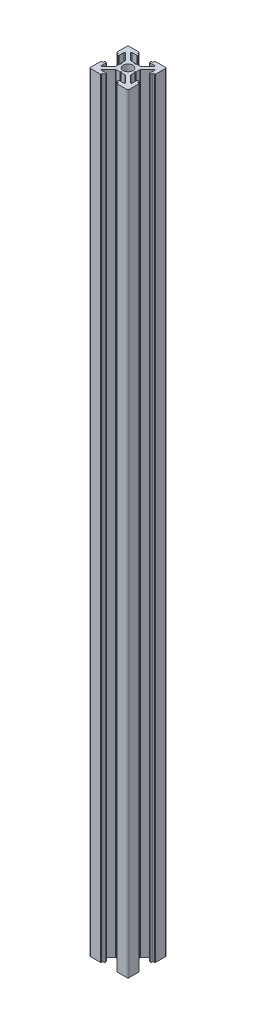
SolidWorks part; units mm, degrees
material "1060 Alloy"
ref_plane "Front Plane" through (0, 0, 0) normal (0, 0, 1) x (1, 0, 0)
ref_plane "Top Plane" through (0, 0, 0) normal (0, 1, 0) x (1, 0, 0)
ref_plane "Right Plane" through (0, 0, 0) normal (1, 0, 0) x (0, 0, -1)
sketch "Sketch1" plane through (0, 0, 0) normal (1, 0, 0) x (0, 0, -1)
  line L0 (0, 0) -> (0, 400)
  dimension "D1" = 400
other "Vuong NHOMDH20X20(1)"
ref_plane "Plane1" through (0, 0, 0) normal (0, 1, 0) x (0, 0, 1)
sketch "Sketch2" plane through (0, 0, 0) normal (0, 1, 0) x (0, 0, 1)
  line L0 (0, 10) -> (0, 0) construction
  line L1 (0, 0) -> (10, 0) construction
  line L2 (0.3857, 3.9) -> (2.3607, 3.9)
  line L3 (2.5729, 3.9879) -> (6.0729, 7.4879)
  line L4 (5.8607, 8) -> (3.4, 8)
  line L5 (3.1, 8.3) -> (3.1, 8.7)
  line L6 (3.4, 9) -> (3.8, 9)
  line L7 (4.1, 9.3) -> (4.1, 9.7)
  line L8 (4.4, 10) -> (9.5, 10)
  line L9 (10, 9.5) -> (10, 4.4)
  line L10 (9.7, 4.1) -> (9.3, 4.1)
  line L11 (9, 3.8) -> (9, 3.4)
  line L12 (8.7, 3.1) -> (8.3, 3.1)
  line L13 (8, 3.4) -> (8, 5.8607)
  line L14 (7.4879, 6.0729) -> (3.9879, 2.5729)
  line L15 (3.9, 2.3607) -> (3.9, 0.3857)
  line L16 (10, 10) -> (0, 0) construction
  line L17 (3.9, -0.3857) -> (3.9, -2.3607)
  line L18 (3.9879, -2.5729) -> (7.4879, -6.0729)
  line L19 (8, -5.8607) -> (8, -3.4)
  line L20 (8.3, -3.1) -> (8.7, -3.1)
  line L21 (9, -3.4) -> (9, -3.8)
  line L22 (9.3, -4.1) -> (9.7, -4.1)
  line L23 (10, -4.4) -> (10, -9.5)
  line L24 (9.5, -10) -> (4.4, -10)
  line L25 (4.1, -9.7) -> (4.1, -9.3)
  line L26 (3.8, -9) -> (3.4, -9)
  line L27 (3.1, -8.7) -> (3.1, -8.3)
  line L28 (3.4, -8) -> (5.8607, -8)
  line L29 (6.0729, -7.4879) -> (2.5729, -3.9879)
  line L30 (2.3607, -3.9) -> (0.3857, -3.9)
  line L31 (10, -10) -> (0, 0) construction
  line L32 (-0.3857, -3.9) -> (-2.3607, -3.9)
  line L33 (-2.5729, -3.9879) -> (-6.0729, -7.4879)
  line L34 (-5.8607, -8) -> (-3.4, -8)
  line L35 (-3.1, -8.3) -> (-3.1, -8.7)
  line L36 (-3.4, -9) -> (-3.8, -9)
  line L37 (-4.1, -9.3) -> (-4.1, -9.7)
  line L38 (-4.4, -10) -> (-9.5, -10)
  line L39 (-10, -9.5) -> (-10, -4.4)
  line L40 (-9.7, -4.1) -> (-9.3, -4.1)
  line L41 (-9, -3.8) -> (-9, -3.4)
  line L42 (-8.7, -3.1) -> (-8.3, -3.1)
  line L43 (-8, -3.4) -> (-8, -5.8607)
  line L44 (-7.4879, -6.0729) -> (-3.9879, -2.5729)
  line L45 (-3.9, -2.3607) -> (-3.9, -0.3857)
  line L46 (-10, -10) -> (0, 0) construction
  line L47 (-3.9, 0.3857) -> (-3.9, 2.3607)
  line L48 (-3.9879, 2.5729) -> (-7.4879, 6.0729)
  line L49 (-8, 5.8607) -> (-8, 3.4)
  line L50 (-8.3, 3.1) -> (-8.7, 3.1)
  line L51 (-9, 3.4) -> (-9, 3.8)
  line L52 (-9.3, 4.1) -> (-9.7, 4.1)
  line L53 (-10, 4.4) -> (-10, 9.5)
  line L54 (-9.5, 10) -> (-4.4, 10)
  line L55 (-4.1, 9.7) -> (-4.1, 9.3)
  line L56 (-3.8, 9) -> (-3.4, 9)
  line L57 (-3.1, 8.7) -> (-3.1, 8.3)
  line L58 (-3.4, 8) -> (-5.8607, 8)
  line L59 (-6.0729, 7.4879) -> (-2.5729, 3.9879)
  line L60 (-2.3607, 3.9) -> (-0.3857, 3.9)
  line L61 (-10, 10) -> (0, 0) construction
  line L62 (-0.3857, 3.9) -> (0, 3.4404)
  line L63 (0, 3.4404) -> (0.3857, 3.9)
  line L64 (3.4404, 0) -> (3.9, -0.3857)
  line L65 (3.9, 0.3857) -> (3.4404, 0)
  line L66 (0, -3.4404) -> (-0.3857, -3.9)
  line L67 (0.3857, -3.9) -> (0, -3.4404)
  line L68 (-3.4404, 0) -> (-3.9, 0.3857)
  line L69 (-3.9, -0.3857) -> (-3.4404, 0)
  arc A0 (4.1, 9.7) -> (4.4, 10) centre (4.4, 9.7) cw
  arc A1 (3.8, 9) -> (4.1, 9.3) centre (3.8, 9.3) ccw
  arc A2 (3.1, 8.7) -> (3.4, 9) centre (3.4, 8.7) cw
  arc A3 (3.4, 8) -> (3.1, 8.3) centre (3.4, 8.3) cw
  arc A4 (10, 4.4) -> (9.7, 4.1) centre (9.7, 4.4) cw
  arc A5 (9.3, 4.1) -> (9, 3.8) centre (9.3, 3.8) ccw
  arc A6 (9, 3.4) -> (8.7, 3.1) centre (8.7, 3.4) cw
  arc A7 (8.3, 3.1) -> (8, 3.4) centre (8.3, 3.4) cw
  arc A8 (3.9879, 2.5729) -> (3.9, 2.3607) centre (4.2, 2.3607) ccw
  arc A9 (2.3607, 3.9) -> (2.5729, 3.9879) centre (2.3607, 4.2) ccw
  arc A10 (8, 5.8607) -> (7.4879, 6.0729) centre (7.7, 5.8607) ccw
  arc A11 (6.0729, 7.4879) -> (5.8607, 8) centre (5.8607, 7.7) ccw
  arc A12 (9.5, 10) -> (10, 9.5) centre (9.5, 9.5) cw
  arc A13 (9.7, -4.1) -> (10, -4.4) centre (9.7, -4.4) cw
  arc A14 (9, -3.8) -> (9.3, -4.1) centre (9.3, -3.8) ccw
  arc A15 (8.7, -3.1) -> (9, -3.4) centre (8.7, -3.4) cw
  arc A16 (8, -3.4) -> (8.3, -3.1) centre (8.3, -3.4) cw
  arc A17 (4.4, -10) -> (4.1, -9.7) centre (4.4, -9.7) cw
  arc A18 (4.1, -9.3) -> (3.8, -9) centre (3.8, -9.3) ccw
  arc A19 (3.4, -9) -> (3.1, -8.7) centre (3.4, -8.7) cw
  arc A20 (3.1, -8.3) -> (3.4, -8) centre (3.4, -8.3) cw
  arc A21 (2.5729, -3.9879) -> (2.3607, -3.9) centre (2.3607, -4.2) ccw
  arc A22 (3.9, -2.3607) -> (3.9879, -2.5729) centre (4.2, -2.3607) ccw
  arc A23 (5.8607, -8) -> (6.0729, -7.4879) centre (5.8607, -7.7) ccw
  arc A24 (7.4879, -6.0729) -> (8, -5.8607) centre (7.7, -5.8607) ccw
  arc A25 (10, -9.5) -> (9.5, -10) centre (9.5, -9.5) cw
  arc A26 (-4.1, -9.7) -> (-4.4, -10) centre (-4.4, -9.7) cw
  arc A27 (-3.8, -9) -> (-4.1, -9.3) centre (-3.8, -9.3) ccw
  arc A28 (-3.1, -8.7) -> (-3.4, -9) centre (-3.4, -8.7) cw
  arc A29 (-3.4, -8) -> (-3.1, -8.3) centre (-3.4, -8.3) cw
  arc A30 (-10, -4.4) -> (-9.7, -4.1) centre (-9.7, -4.4) cw
  arc A31 (-9.3, -4.1) -> (-9, -3.8) centre (-9.3, -3.8) ccw
  arc A32 (-9, -3.4) -> (-8.7, -3.1) centre (-8.7, -3.4) cw
  arc A33 (-8.3, -3.1) -> (-8, -3.4) centre (-8.3, -3.4) cw
  arc A34 (-3.9879, -2.5729) -> (-3.9, -2.3607) centre (-4.2, -2.3607) ccw
  arc A35 (-2.3607, -3.9) -> (-2.5729, -3.9879) centre (-2.3607, -4.2) ccw
  arc A36 (-8, -5.8607) -> (-7.4879, -6.0729) centre (-7.7, -5.8607) ccw
  arc A37 (-6.0729, -7.4879) -> (-5.8607, -8) centre (-5.8607, -7.7) ccw
  arc A38 (-9.5, -10) -> (-10, -9.5) centre (-9.5, -9.5) cw
  arc A39 (-9.7, 4.1) -> (-10, 4.4) centre (-9.7, 4.4) cw
  arc A40 (-9, 3.8) -> (-9.3, 4.1) centre (-9.3, 3.8) ccw
  arc A41 (-8.7, 3.1) -> (-9, 3.4) centre (-8.7, 3.4) cw
  arc A42 (-8, 3.4) -> (-8.3, 3.1) centre (-8.3, 3.4) cw
  arc A43 (-4.4, 10) -> (-4.1, 9.7) centre (-4.4, 9.7) cw
  arc A44 (-4.1, 9.3) -> (-3.8, 9) centre (-3.8, 9.3) ccw
  arc A45 (-3.4, 9) -> (-3.1, 8.7) centre (-3.4, 8.7) cw
  arc A46 (-3.1, 8.3) -> (-3.4, 8) centre (-3.4, 8.3) cw
  arc A47 (-2.5729, 3.9879) -> (-2.3607, 3.9) centre (-2.3607, 4.2) ccw
  arc A48 (-3.9, 2.3607) -> (-3.9879, 2.5729) centre (-4.2, 2.3607) ccw
  arc A49 (-5.8607, 8) -> (-6.0729, 7.4879) centre (-5.8607, 7.7) ccw
  arc A50 (-7.4879, 6.0729) -> (-8, 5.8607) centre (-7.7, 5.8607) ccw
  arc A51 (-10, 9.5) -> (-9.5, 10) centre (-9.5, 9.5) cw
  circle A52 centre (0, 0) radius 2.5
  point P3 (0, 0)
  point P23 (4.1, 10)
  point P26 (4.1, 9)
  point P33 (10, 4.1)
  point P46 (8, 6.585)
  point P179 (0, 0)
  point P188 (0, 0)
  dimension "D8" = 0.3
  dimension "D9" = 0.5
  dimension "D11" = 5
  dimension "D1" = 10
  dimension "D2" = 8.2
  dimension "D3" = 6.2
  dimension "D4" = 2
  dimension "D5" = 1
  dimension "D6" = 13.17
  dimension "D7" = 7.8
  dimension "D12" = 0.6
  dimension "D13" = 80
  dimension "D10" = 4
  dimension "D14" = 4
